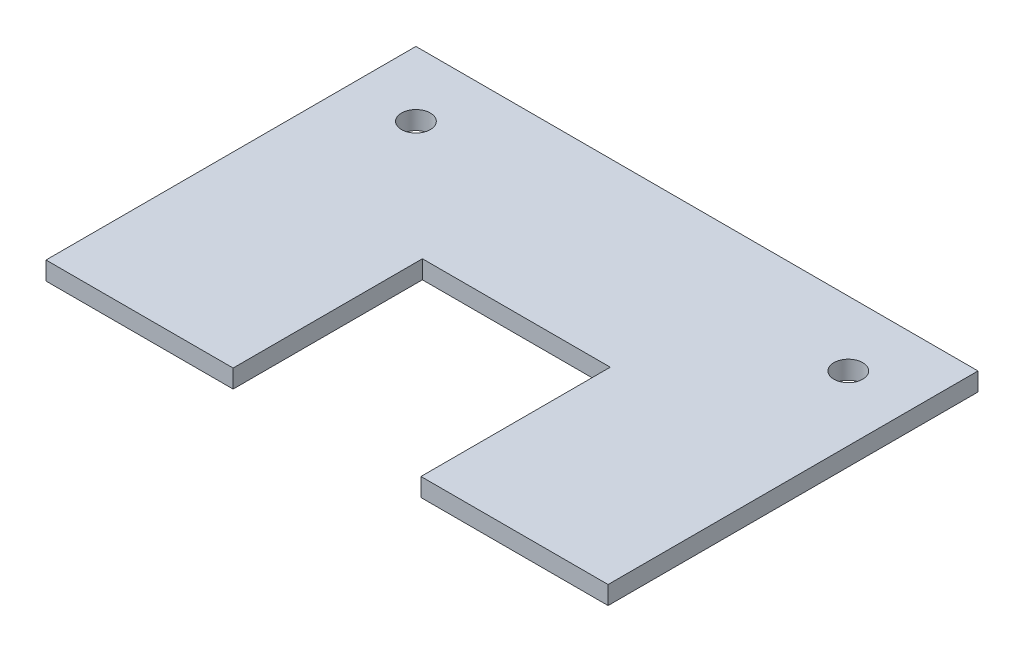
SolidWorks part; units mm, degrees
ref_plane "前视基准面" through (0, 0, 0) normal (0, 0, 1) x (1, 0, 0)
ref_plane "上视基准面" through (0, 0, 0) normal (0, 1, 0) x (1, 0, 0)
ref_plane "右视基准面" through (0, 0, 0) normal (1, 0, 0) x (0, 0, -1)
sketch "草图1" plane through (0, 0, 0) normal (0, 1, 0) x (1, 0, 0)
  line L0 (29.25, 40.761) -> (29.25, -53.1198) construction
  line L1 (0, 0) -> (58.5, 0)
  line L2 (0, 0) -> (0, -38.5)
  line L3 (0, -38.5) -> (19.475, -38.5)
  line L4 (58.5, 0) -> (58.5, -38.5)
  line L6 (19.475, -38.5) -> (19.475, -18.8)
  line L7 (19.475, -18.8) -> (39.025, -18.8)
  line L8 (39.025, -38.5) -> (39.025, -18.8)
  line L9 (39.025, -38.5) -> (58.5, -38.5)
  dimension "D1" = 58.5
  dimension "D2" = 38.5
  dimension "D3" = 19.55
  dimension "D4" = 19.7
extrude "凸台-拉伸1" add sketch "草图1" along normal blind 1.9
sketch "草图2" plane through (0, 0, 0) normal (0, -1, 0) x (1, 0, 0)
  line L0 (58.5, 0) -> (0, 0) construction
  line L1 (58.5, 38.5) -> (58.5, 0) construction
  line L2 (0, 0) -> (0, 38.5) construction
  circle A0 centre (51.75, 6.75) radius 1.5
  circle A1 centre (6.75, 6.75) radius 1.5
  point P8 (0, 0)
  point P9 (0, 0)
  dimension "D1" = 6.75
  dimension "D2" = 6.75
  dimension "D3" = 3
  dimension "D4" = 6.75
extrude "切除-拉伸1" cut sketch "草图2" against normal up to next
